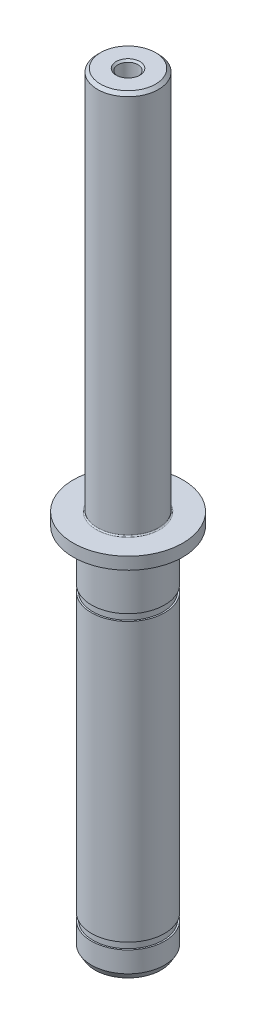
SolidWorks part; units mm, degrees
material "AISI 1020"
ref_plane "Přední rovina" through (0, 0, 0) normal (0, 0, 1) x (1, 0, 0)
ref_plane "Horní rovina" through (0, 0, 0) normal (0, 1, 0) x (1, 0, 0)
ref_plane "Pravá rovina" through (0, 0, 0) normal (1, 0, 0) x (0, 0, -1)
sketch "Skica1" plane through (0, 0, 0) normal (0, 0, 1) x (1, 0, 0)
  line L0 (0, 0) -> (0, 50000) construction
  line L1 (-6, 0) -> (-6, 4.4)
  line L2 (-6, 60.5) -> (-9, 60.5)
  line L3 (-9, 60.5) -> (-9, 62.5)
  line L4 (-9, 62.5) -> (-5, 62.5)
  line L5 (-5, 62.5) -> (-5, 125.5)
  line L6 (-5, 125.5) -> (0, 125.5)
  line L7 (-6, 0) -> (0, 0)
  line L8 (0, 125.5) -> (0, 0)
  line L9 (-6, 5.5) -> (-5.75, 5.5)
  line L10 (-5.75, 5.5) -> (-5.75, 4.4)
  line L11 (-5.75, 4.4) -> (-6, 4.4)
  line L12 (-6, 5.5) -> (-6, 51.1)
  line L13 (-6, 52.2) -> (-5.75, 52.2)
  line L14 (-5.75, 52.2) -> (-5.75, 51.1)
  line L15 (-5.75, 51.1) -> (-6, 51.1)
  line L16 (-6, 52.2) -> (-6, 60.5)
  dimension "D1" = 10
  dimension "D2" = 12
  dimension "D3" = 18
  dimension "D4" = 2
  dimension "D5" = 63
  dimension "D6" = 60.5
  dimension "D7" = 1.1
  dimension "D8" = 11.5
  dimension "D9" = 4.4
  dimension "D10" = 1.1
  dimension "D11" = 8.3
  dimension "D12" = 5.75
revolve "Rotovat1" add sketch "Skica1" angle 360 about L0
chamfer "Zkosení1" distance 0.5 angle 45 1 edges at (0, 125.5, -5)
chamfer "Zkosení2" distance 1 angle 30 1 edges at (0, 0, -6)
ref_plane "Rovina2" through (0, 0, 2.9) normal (0, 0, 1) x (1, 0, 0)
fillet "Zaoblit3" radius 0.2 1 edges at (0, 62.5, -5)
sketch "Skica5" plane through (0, 125.5, 0) normal (0, 1, 0) x (1, 0, 0)
  point P0 (0, 0)
hole_wizard "M4 závit1" positions "Skica5" profile "Skica6" tap size "M4" standard "ISO"
cosmetic thread "Závit díry1" parameters "D1"=10, "D2"=4
sketch "Skica6" plane through (0, 125.5, 0) normal (1, 0, 0) x (0, 0, 1)
  line L0 (0, 0) -> (0, 12.9914)
  line L1 (0, 12.9914) -> (1.65, 12)
  line L2 (1.65, 12) -> (1.65, 0)
  line L5 (1.65, 0) -> (0, 0)
  line L10 (0, 12.9914) -> (-1.65, 12) construction
  line L11 (0, -6.35) -> (0, 107.95) construction
  dimension "Průměr závitníku" = 3.3
  dimension "Hloubka závitníku" = 12
  dimension "Úhel vrtání" = 118
chamfer "Zkosení4" distance 0.3 angle 45 1 edges at (0, 125.5, 1.65)
